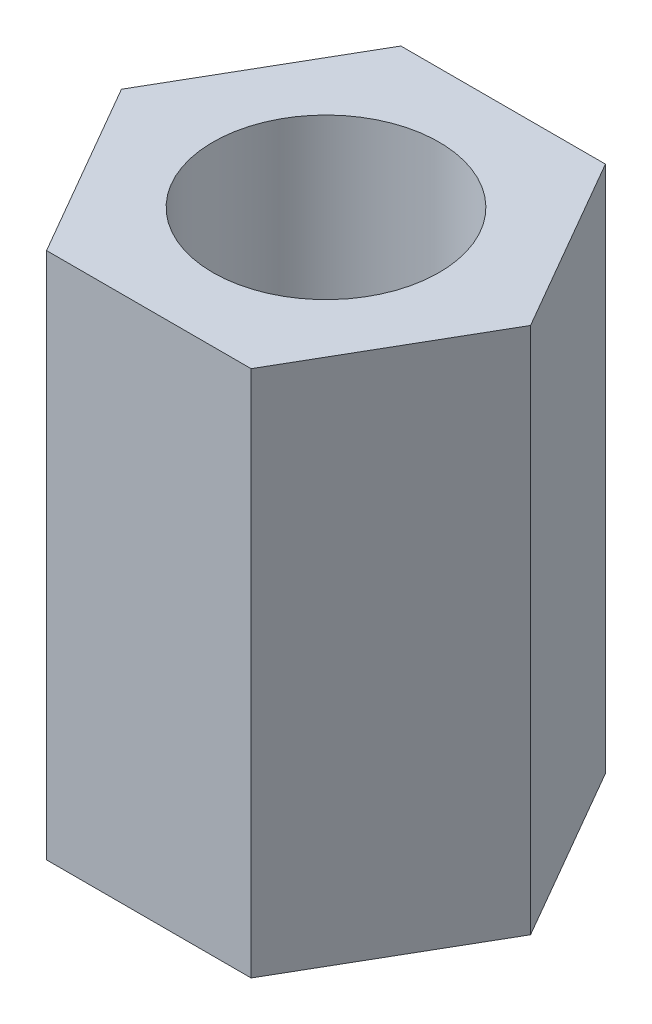
SolidWorks part; units mm, degrees
material "黄铜"
ref_plane "前视基准面" through (0, 0, 0) normal (0, 0, 1) x (1, 0, 0)
ref_plane "上视基准面" through (0, 0, 0) normal (0, 1, 0) x (1, 0, 0)
ref_plane "右视基准面" through (0, 0, 0) normal (1, 0, 0) x (0, 0, -1)
other "Configuration Table"
sketch "草图1" plane through (0, 0, 0) normal (0, 1, 0) x (1, 0, 0)
  line L0 (-2.7135, 0) -> (2.7135, 0) construction
  line L1 (1.3568, -2.35) -> (2.7135, 0)
  line L2 (2.7135, 0) -> (1.3568, 2.35)
  line L3 (1.3568, 2.35) -> (-1.3568, 2.35)
  line L4 (-1.3568, 2.35) -> (-2.7135, 0)
  line L5 (-2.7135, 0) -> (-1.3568, -2.35)
  line L6 (-1.3568, -2.35) -> (1.3568, -2.35)
  circle A0 centre (0, 0) radius 2.35 construction
  circle A1 centre (0, 0) radius 1.5
  point P13 (0, 0)
  dimension "D2" = 3
  dimension "D1" = 4.7
extrude "凸台-拉伸1" add sketch "草图1" along normal blind 7
